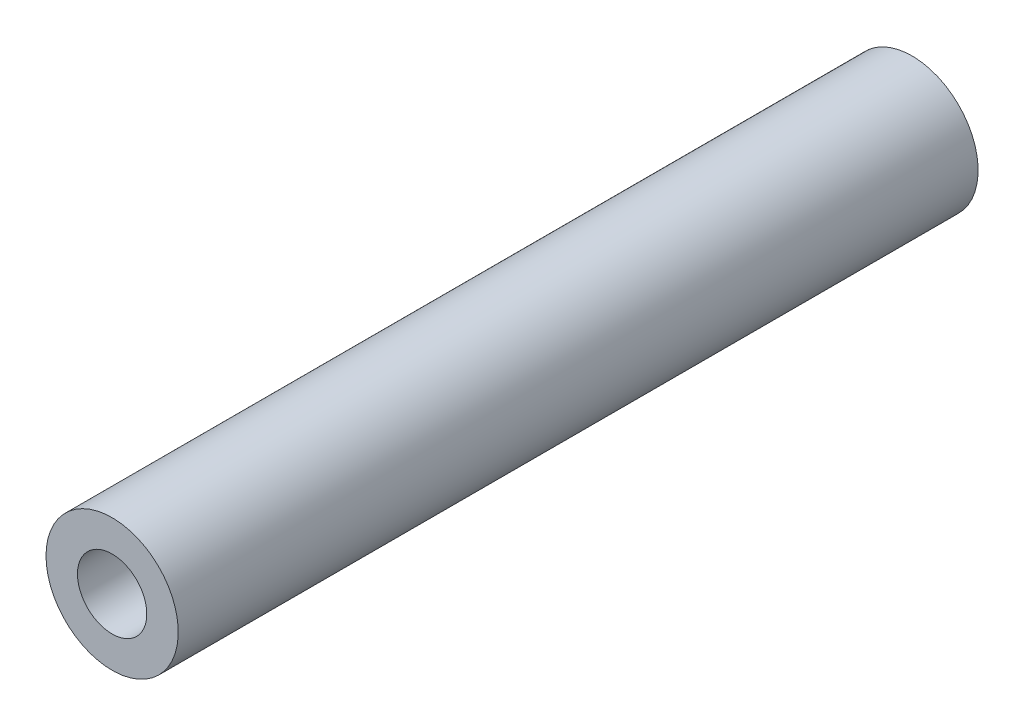
SolidWorks part; units mm, degrees
material "6061-T6 (SS)"
ref_plane "Front Plane" through (0, 0, 0) normal (0, 0, 1) x (1, 0, 0)
ref_plane "Top Plane" through (0, 0, 0) normal (0, 1, 0) x (1, 0, 0)
ref_plane "Right Plane" through (0, 0, 0) normal (1, 0, 0) x (0, 0, -1)
sketch "Sketch1" plane through (0, 0, 0) normal (0, 0, 1) x (1, 0, 0)
  circle A0 centre (0, 0) radius 1.5748
  circle A1 centre (0, 0) radius 1.5748
  circle A2 centre (0, 0) radius 0.8255
  dimension "D1" = 3.1496
  dimension "D2" = 1.651
extrude "Extrude1" add sketch "Sketch1" along normal blind 19.05 contours A0 A2
